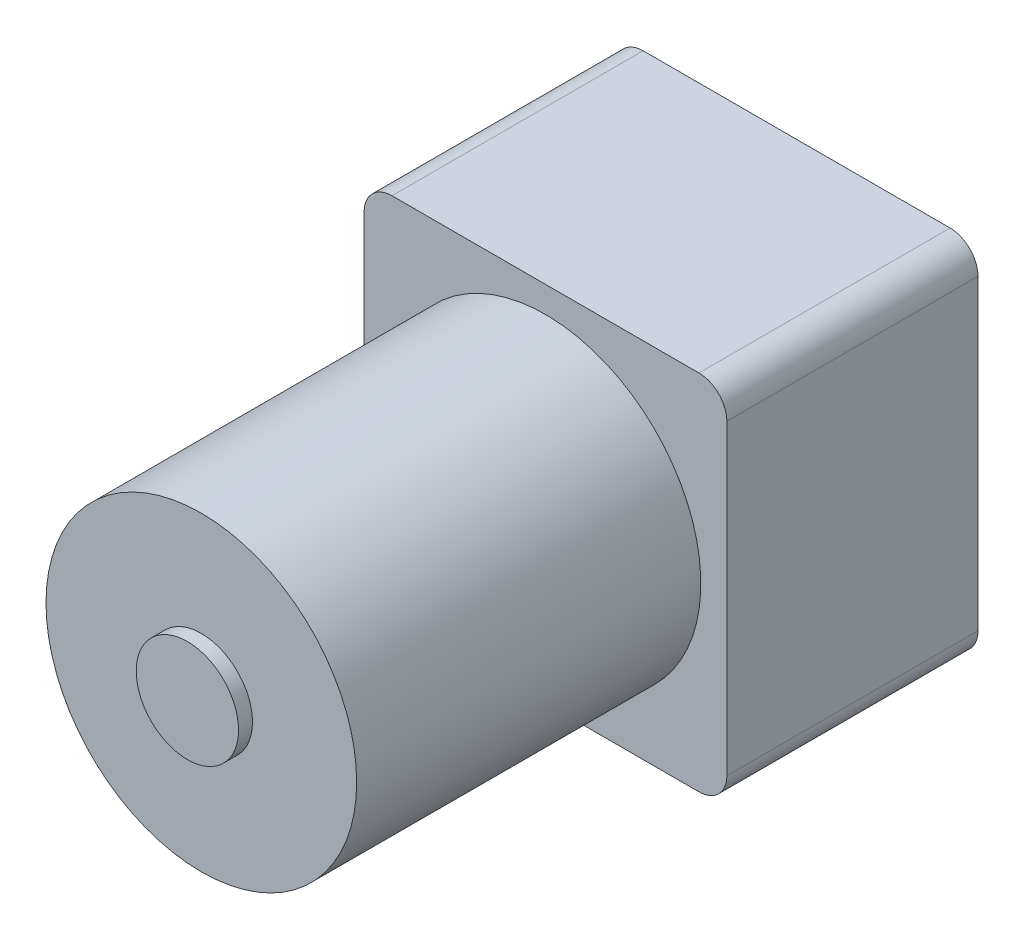
SolidWorks part; units mm, degrees
ref_plane "Plan de face" through (0, 0, 0) normal (0, 0, 1) x (1, 0, 0)
ref_plane "Plan de dessus" through (0, 0, 0) normal (0, 1, 0) x (1, 0, 0)
ref_plane "Plan de droite" through (0, 0, 0) normal (1, 0, 0) x (0, 0, -1)
sketch "Esquisse1" plane through (0, 0, 0) normal (0, 0, 1) x (1, 0, 0)
  line L1 (-21.2635, 17.0512) -> (11.7365, 17.0512)
  line L2 (-24.2635, 14.0512) -> (-24.2635, -18.9488)
  line L3 (-21.2635, -21.9488) -> (11.7365, -21.9488)
  line L4 (14.7365, 14.0512) -> (14.7365, -18.9488)
  arc A0 (11.7365, 17.0512) -> (14.7365, 14.0512) centre (11.7365, 14.0512) cw
  arc A1 (-21.2635, 17.0512) -> (-24.2635, 14.0512) centre (-21.2635, 14.0512) ccw
  arc A2 (-24.2635, -18.9488) -> (-21.2635, -21.9488) centre (-21.2635, -18.9488) ccw
  arc A3 (11.7365, -21.9488) -> (14.7365, -18.9488) centre (11.7365, -18.9488) ccw
  point P8 (-24.2635, 17.0512)
  point P11 (-24.2635, -21.9488)
  point P14 (14.7365, -21.9488)
  dimension "D3" = 3
  dimension "D1" = 39
  dimension "D2" = 39
extrude "Extrusion1" add sketch "Esquisse1" along normal blind 27
sketch "Esquisse2" plane through (0, 0, 27) normal (0, 0, 1) x (1, 0, 0)
  line L0 (14.7365, -18.9488) -> (14.7365, 14.0512) construction
  line L1 (11.7365, 17.0512) -> (-21.2635, 17.0512) construction
  circle A0 centre (-4.7635, -2.4488) radius 16.7
  dimension "D1" = 19.5
  dimension "D2" = 19.5
extrude "Extrusion2" add sketch "Esquisse2" along normal blind 37
sketch "Esquisse3" plane through (0, 0, 64) normal (0, 0, 1) x (1, 0, 0)
  line L0 (14.7365, -18.9488) -> (14.7365, 14.0512) construction
  line L1 (11.7365, 17.0512) -> (-21.2635, 17.0512) construction
  circle A0 centre (-4.7635, -2.4488) radius 5.5
  dimension "D1" = 19.5
  dimension "D2" = 19.5
extrude "Extrusion3" add sketch "Esquisse3" along normal blind 1.5
sketch "Esquisse4" plane through (0, 0, 0) normal (0, 0, -1) x (-1, 0, 0)
  line L0 (-11.7365, 17.0512) -> (21.2635, 17.0512) construction
  line L1 (-11.2365, 13.5512) -> (20.7635, 13.5512) construction
  line L2 (-11.2365, 13.5512) -> (-11.2365, -18.4488) construction
  line L3 (-11.2365, -18.4488) -> (20.7635, -18.4488) construction
  line L4 (20.7635, 13.5512) -> (20.7635, -18.4488) construction
  line L5 (24.2635, 14.0512) -> (24.2635, -18.9488) construction
  circle A0 centre (-11.2365, 13.5512) radius 1.35
  circle A1 centre (20.7635, 13.5512) radius 1.35
  circle A2 centre (20.7635, -18.4488) radius 1.35
  circle A3 centre (-11.2365, -18.4488) radius 1.35
  dimension "D1" = 32
  dimension "D2" = 32
  dimension "D3" = 3.5
  dimension "D4" = 3.5
extrude "Extrusion4" cut sketch "Esquisse4" against normal blind 10
sketch "Esquisse5" plane through (0, 0, 0) normal (0, 0, -1) x (-1, 0, 0)
  line L0 (24.2635, 14.0512) -> (24.2635, -18.9488) construction
  line L1 (-11.7365, 17.0512) -> (21.2635, 17.0512) construction
  circle A0 centre (4.7635, -2.4488) radius 5.5
  dimension "D1" = 19.5
  dimension "D2" = 19.5
extrude "Extrusion5" add sketch "Esquisse5" along normal blind 1.5
sketch "Esquisse6" plane through (0, 0, -1.5) normal (0, 0, -1) x (-1, 0, 0)
  line L0 (24.2635, 14.0512) -> (24.2635, -18.9488) construction
  line L1 (-11.7365, 17.0512) -> (21.2635, 17.0512) construction
  circle A0 centre (4.7635, -2.4488) radius 2
  dimension "D1" = 19.5
  dimension "D2" = 19.5
extrude "Extrusion6" add sketch "Esquisse6" along normal blind 8.5
